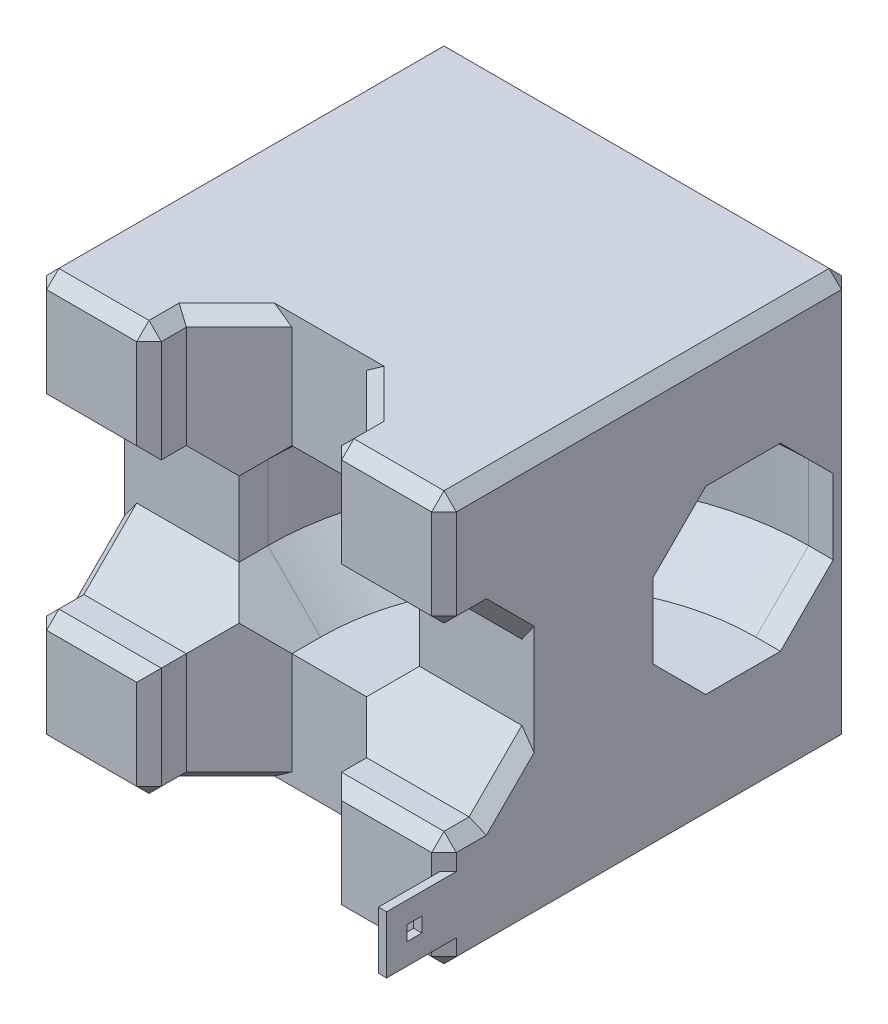
SolidWorks part; units mm, degrees
ref_plane "Front" through (0, 0, 0) normal (0, 0, 1) x (1, 0, 0)
ref_plane "Top" through (0, 0, 0) normal (0, 1, 0) x (1, 0, 0)
ref_plane "Right" through (0, 0, 0) normal (1, 0, 0) x (0, 0, -1)
sketch "Sketch1" plane through (0, 0, 0) normal (0, 0, 1) x (1, 0, 0)
  line L1 (0, 0) -> (50, 0)
  line L2 (0, 0) -> (0, 50)
  line L3 (0, 50) -> (50, 50)
  line L4 (50, 0) -> (50, 50)
  dimension "D1" = 50
extrude "Boss-Extrude1" add sketch "Sketch1" along normal blind 50
sketch "Sketch2" plane through (0, 0, 0) normal (0, 1, 0) x (0, 0, 1)
  line L0 (50, 0) -> (50, 50) construction
  line L10 (39, 36) -> (61, 36) construction
  line L11 (39, 36) -> (39, 14) construction
  line L12 (39, 14) -> (61, 14) construction
  line L13 (61, 36) -> (61, 14) construction
  line L14 (61, 29.5563) -> (54.5563, 36)
  line L15 (39, 36) -> (61, 14) construction
  line L16 (54.5563, 36) -> (45.4437, 36)
  line L17 (39, 14) -> (61, 36) construction
  line L26 (45.4437, 36) -> (39, 29.5563)
  line L27 (39, 29.5563) -> (39, 20.4437)
  line L28 (39, 20.4437) -> (45.4437, 14)
  line L29 (45.4437, 14) -> (54.5563, 14)
  line L30 (54.5563, 14) -> (61, 20.4437)
  line L31 (61, 20.4437) -> (61, 29.5563)
  circle A1 centre (50, 25) radius 11 construction
  point P5 (50, 25)
  dimension "D1" = 22
sketch "Sketch6" plane through (0, 0, 0) normal (1, 0, 0) x (0, 0, -1)
  line L0 (-50, 25) -> (0, 25) construction
  line L1 (-61, 29.5563) -> (-61, 20.4437)
  line L2 (-61, 20.4437) -> (-54.5563, 14)
  line L3 (-54.5563, 14) -> (-45.4437, 14)
  line L4 (-45.4437, 14) -> (-39, 20.4437)
  line L5 (-39, 20.4437) -> (-39, 29.5563)
  line L6 (-39, 29.5563) -> (-45.4437, 36)
  line L7 (-45.4437, 36) -> (-54.5563, 36)
  line L8 (-54.5563, 36) -> (-61, 29.5563)
  line L9 (0, 0) -> (0, 50) construction
  line L10 (-50, 50) -> (-50, 0) construction
  circle A0 centre (-50, 25) radius 11 construction
  dimension "D1" = 22
extrude "Cut-Extrude3" cut sketch "Sketch2" along normal through all
extrude "Cut-Extrude4" cut sketch "Sketch6" along normal through all
ref_plane "Plane1" through (0, 25, 0) normal (0, -1, 0) x (-1, 0, 0)
sketch "Sketch8" plane through (50, 0, 0) normal (1, 0, 0) x (0, 0, -1)
  line L0 (-25, 0) -> (-25, 25) construction
  line L1 (-2.5, 14) -> (-24.5, 14) construction
  line L2 (-2.5, 14) -> (-2.5, 36) construction
  line L3 (-2.5, 36) -> (-24.5, 36) construction
  line L4 (-24.5, 14) -> (-24.5, 36) construction
  line L5 (-2.5, 14) -> (-24.5, 36) construction
  line L6 (-2.5, 36) -> (-24.5, 14) construction
  line L8 (-50, 0) -> (0, 0) construction
  line L10 (-25, 25) -> (-13.5, 25) construction
  line L11 (-2.5, 29.5563) -> (-8.9437, 36)
  line L12 (-8.9437, 36) -> (-18.0563, 36)
  line L13 (-18.0563, 36) -> (-24.5, 29.5563)
  line L14 (-24.5, 29.5563) -> (-24.5, 20.4437)
  line L15 (-24.5, 20.4437) -> (-18.0563, 14)
  line L16 (-18.0563, 14) -> (-8.9437, 14)
  line L17 (-8.9437, 14) -> (-2.5, 20.4437)
  line L18 (-2.5, 20.4437) -> (-2.5, 29.5563)
  line L19 (-13.5, 25) -> (0, 25) construction
  line L20 (0, 0) -> (0, 50) construction
  circle A0 centre (-13.5, 25) radius 11 construction
  point P0 (-13.5, 25)
  dimension "D1" = 22
  dimension "D2" = 2.5
sketch "Sketch9" plane through (0, 25, 0) normal (0, -1, 0) x (-1, 0, 0)
  line L0 (-50, -13.5) -> (-47, -13.5)
  line L1 (-25, -35.5) -> (-25, -50)
  line L2 (-36, -50) -> (-14, -50) construction
  arc A0 (-47, -13.5) -> (-25, -35.5) centre (-47, -35.5) cw
  dimension "D2" = 3
sweep "Cut-Sweep5" cut profiles "Sketch8" path "Sketch9"
chamfer "Chamfer1" distance 1.5 angle 45 40 edges at (25, 50, 0) (32.7782, 50, 42.2218) (36, 50, 47.7218) (0, 32.7782, 42.2218) (0, 36, 47.7218) (7, 36, 50) (0, 43, 50) (17.2218, 50, 42.2218) (14, 50, 47.7218) (14, 43, 50) (7, 50, 50) (0, 50, 25) (0, 25, 0) (0, 17.2218, 42.2218) (0, 14, 47.7218) (43, 50, 50) (36, 43, 50) (43, 36, 50) (50, 32.7782, 42.2218) (50, 36, 47.7218) (50, 43, 50) (50, 50, 25) (50, 25, 0) (0, 7, 50) (17.2218, 0, 42.2218) (14, 0, 47.7218) (7, 14, 50) (14, 7, 50) (7, 0, 50) (0, 0, 25) (25, 0, 0) (32.7782, 0, 42.2218) (36, 0, 47.7218) (36, 7, 50) (43, 14, 50) (50, 17.2218, 42.2218) (50, 14, 47.7218) (50, 0, 25) (50, 7, 50) (43, 0, 50)
sketch "Sketch10" plane through (0, 0, 50) normal (0, 0, 1) x (1, 0, 0)
  line L0 (50, 12.5) -> (50, 1.5) construction
  line L1 (50, 10.5) -> (49, 10.5)
  line L2 (50, 10.5) -> (50, 3.5)
  line L3 (50, 3.5) -> (49, 3.5)
  line L4 (49, 10.5) -> (49, 3.5)
  point P6 (50, 7)
  dimension "D1" = 1
  dimension "D2" = 7
extrude "Boss-Extrude2" add sketch "Sketch10" along normal blind 7 and the other way blind 10
sketch "Sketch11" plane through (50, 0, 0) normal (1, 0, 0) x (0, 0, -1)
  line L0 (-54.5, 7) -> (-57, 7) construction
  line L1 (-54.5, 6.1) -> (-52.7, 6.1)
  line L2 (-54.5, 6.1) -> (-54.5, 7.9)
  line L3 (-54.5, 7.9) -> (-52.7, 7.9)
  line L4 (-52.7, 6.1) -> (-52.7, 7.9)
  line L5 (-57, 3.5) -> (-57, 10.5) construction
  dimension "D1" = 2.5
  dimension "D2" = 1.8
extrude "Cut-Extrude5" cut sketch "Sketch11" against normal blind 7
